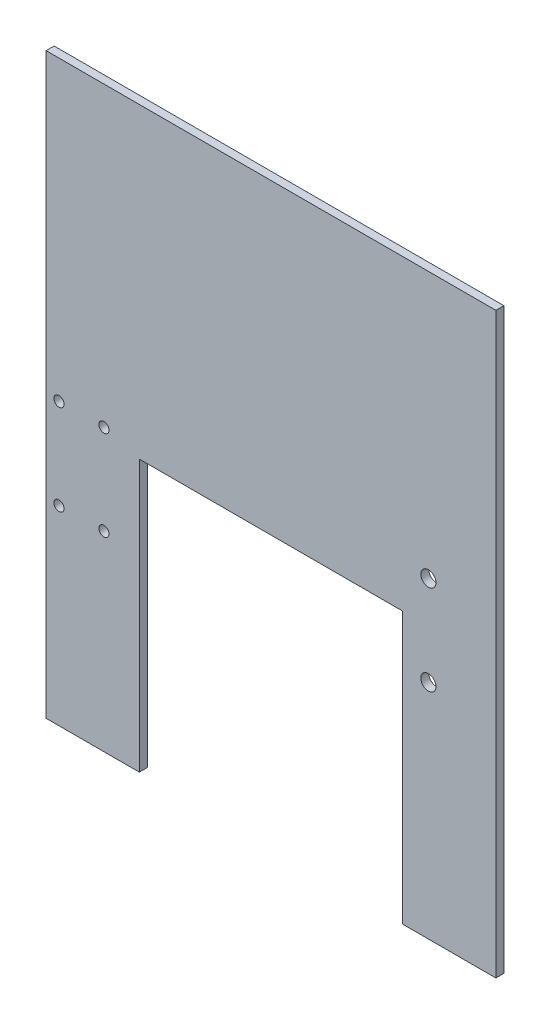
SolidWorks part; units mm, degrees
ref_plane "Front Plane" through (0, 0, 0) normal (0, 0, 1) x (1, 0, 0)
ref_plane "Top Plane" through (0, 0, 0) normal (0, 1, 0) x (1, 0, 0)
ref_plane "Right Plane" through (0, 0, 0) normal (1, 0, 0) x (0, 0, -1)
sketch "Sketch1" plane through (0, 0, 0) normal (0, 0, 1) x (1, 0, 0)
  line L0 (0, 0) -> (0, 228.6)
  line L1 (0, 228.6) -> (177.8, 228.6)
  line L2 (177.8, 228.6) -> (177.8, 0)
  line L3 (177.8, 0) -> (140.97, 0)
  line L4 (140.97, 0) -> (140.97, 107.188)
  line L5 (140.97, 107.188) -> (36.83, 107.188)
  line L6 (36.83, 107.188) -> (36.83, 0)
  line L7 (36.83, 0) -> (0, 0)
  dimension "D1" = 177.8
  dimension "D2" = 228.6
  dimension "D3" = 36.83
  dimension "D4" = 36.83
  dimension "D6" = 107.188
extrude "Boss-Extrude1" add sketch "Sketch1" along normal blind 3.175
ref_plane "Plane1" through (0, 0, 0) normal (0, 0, -1) x (-1, 0, 0)
sketch "Sketch2" plane through (0, 0, 0) normal (0, 0, -1) x (-1, 0, 0)
  line L0 (-36.83, 107.188) -> (-36.83, 111.0716) construction
  line L5 (-22.86, 111.0716) -> (-5.0809, 111.0716)
  line L6 (-36.83, 111.0716) -> (-22.86, 111.0716) construction
  line L16 (-177.8, 0) -> (-241.2544, 0)
  line L17 (-140.97, 0) -> (-177.8, 0) construction
  line L18 (-241.2544, 0) -> (-241.2544, 228.6)
  line L19 (-177.8, 228.6) -> (0, 228.6) construction
  line L20 (0, 0) -> (-12.7245, 0)
  line L21 (0, 0) -> (-36.83, 0) construction
  line L23 (-22.86, 111.0716) -> (-22.86, 75.5116)
  line L25 (-5.0809, 111.0716) -> (-5.0809, 75.3341)
  circle A0 centre (-22.86, 111.0716) radius 2
  circle A1 centre (-5.0809, 111.0716) radius 2
  circle A2 centre (-22.86, 75.5116) radius 2
  circle A3 centre (-5.0809, 75.3341) radius 2
  point P16 (-22.86, 75.5116)
  point P18 (-22.86, 111.0716)
  point P19 (-5.0809, 111.0716)
  point P20 (-5.0809, 75.3341)
  point P43 (-22.86, 75.5116)
  dimension "D1" = 35.56
  dimension "D2" = 17.78
  dimension "D3" = 13.97
extrude "Cut-Extrude1" cut sketch "Sketch2" against normal blind 3.175
sketch "Sketch3" plane through (0, 0, 0) normal (0, 0, -1) x (-1, 0, 0)
  line L0 (-140.97, 0) -> (-177.8, 0) construction
  line L11 (-140.97, 107.188) -> (-177.8, 107.188) construction
  line L12 (-177.8, 0) -> (-177.8, 228.6) construction
  line L13 (-177.8, 107.188) -> (-177.8, 87.884) construction
  line L14 (-177.8, 87.884) -> (-140.97, 87.884) construction
  line L15 (-140.97, 107.188) -> (-140.97, 0) construction
  line L16 (-140.97, 87.884) -> (-140.97, 123.444) construction
  line L17 (-140.97, 123.444) -> (-151.1225, 123.444) construction
  line L18 (-151.1225, 123.444) -> (-151.1225, 87.884) construction
  circle A4 centre (-151.1225, 123.444) radius 3
  circle A5 centre (-151.1225, 87.884) radius 3
  dimension "D1" = 87.884
  dimension "D5" = 35.56
extrude "Cut-Extrude2" cut sketch "Sketch3" against normal blind 5.08
